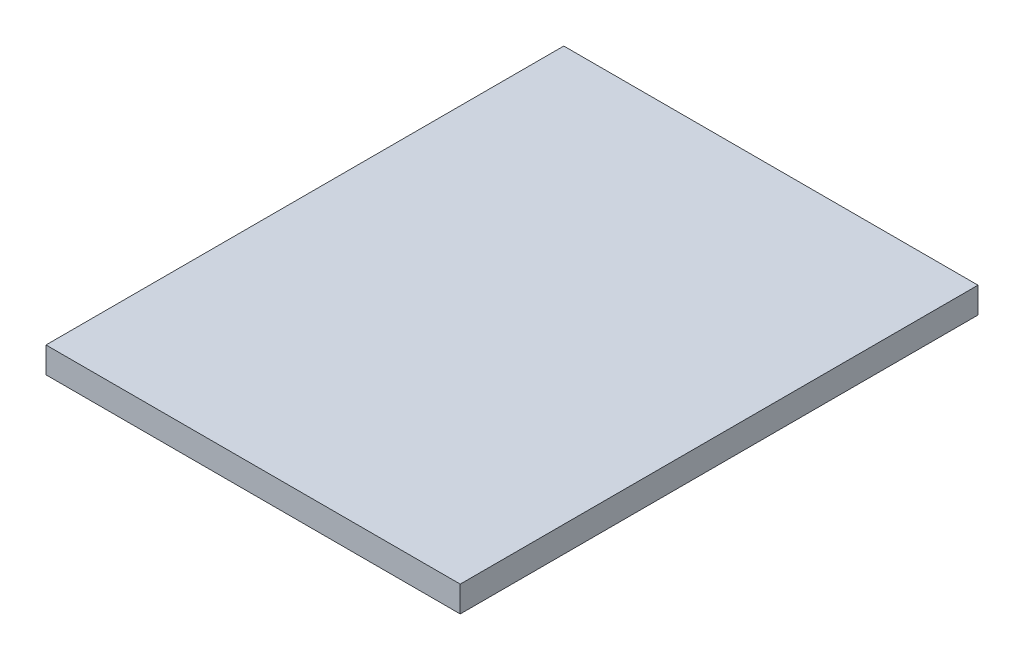
SolidWorks part; units mm, degrees
ref_plane "Front Plane" through (0, 0, 0) normal (0, 0, 1) x (1, 0, 0)
ref_plane "Top Plane" through (0, 0, 0) normal (0, 1, 0) x (1, 0, 0)
ref_plane "Right Plane" through (0, 0, 0) normal (1, 0, 0) x (0, 0, -1)
sketch "Sketch1" plane through (0, 0, 0) normal (0, 1, 0) x (1, 0, 0)
  line L0 (0, 0) -> (40.64, 0)
  line L1 (0, 0) -> (0, 50.8)
  line L2 (0, 50.8) -> (40.64, 50.8)
  line L3 (40.64, 50.8) -> (40.64, 0)
  dimension "D1" = 40.64
  dimension "D2" = 50.8
extrude "Boss-Extrude1" add sketch "Sketch1" along normal blind 2.54
